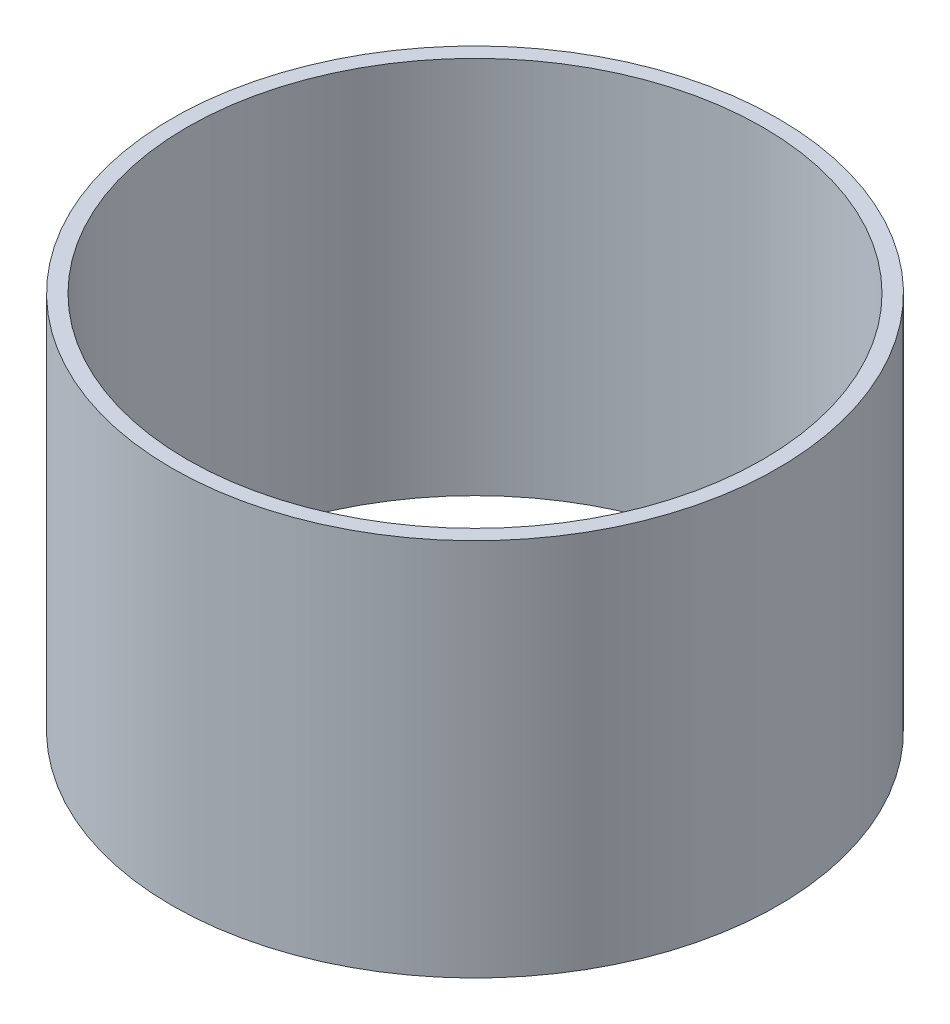
SolidWorks part; units mm, degrees
ref_plane "Front Plane" through (0, 0, 0) normal (0, 0, 1) x (1, 0, 0)
ref_plane "Top Plane" through (0, 0, 0) normal (0, 1, 0) x (1, 0, 0)
ref_plane "Right Plane" through (0, 0, 0) normal (1, 0, 0) x (0, 0, -1)
sketch "Sketch1" plane through (0, 0, 0) normal (0, 1, 0) x (1, 0, 0)
  circle A0 centre (0, 0) radius 38
  circle A1 centre (0, 0) radius 40
  dimension "D1" = 80
  dimension "D2" = 2
extrude "Boss-Extrude1" add sketch "Sketch1" along normal blind 50
